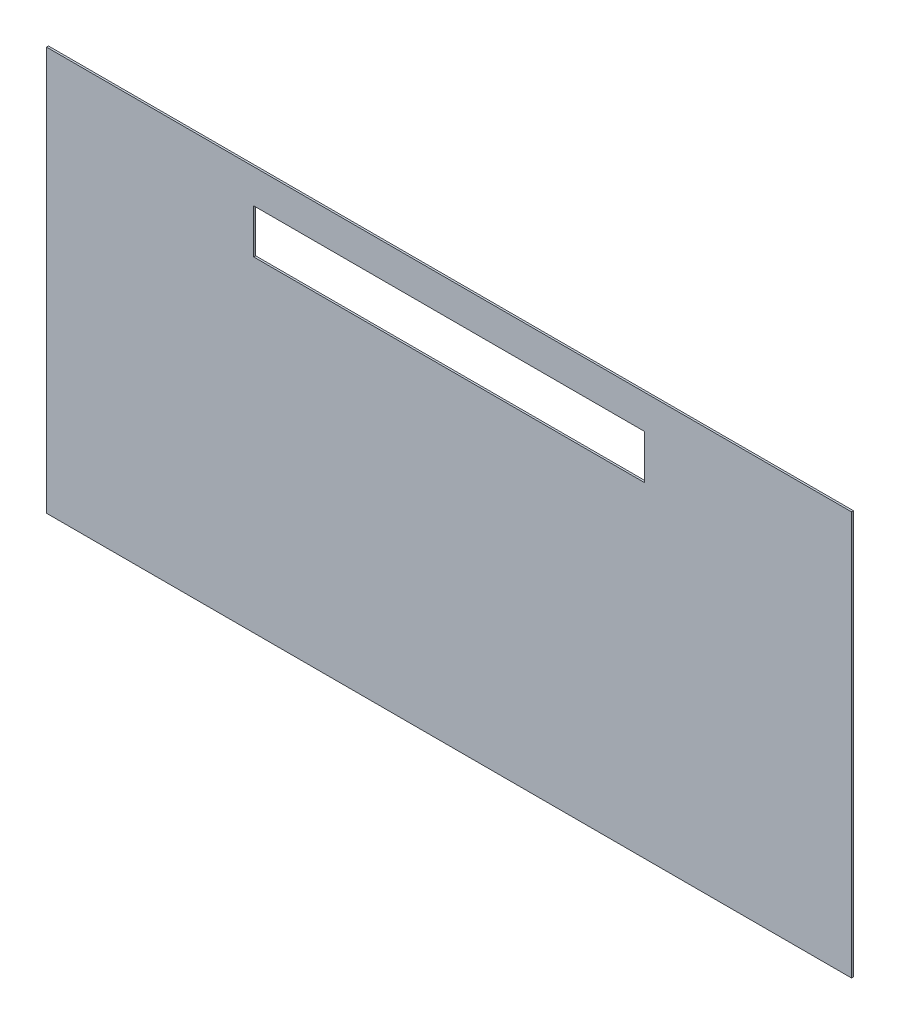
SolidWorks part; units mm, degrees
ref_plane "Front Plane" through (0, 0, 0) normal (0, 0, 1) x (1, 0, 0)
ref_plane "Top Plane" through (0, 0, 0) normal (0, 1, 0) x (1, 0, 0)
ref_plane "Right Plane" through (0, 0, 0) normal (1, 0, 0) x (0, 0, -1)
other "Configuration Table"
sketch "Sketch1" plane through (0, 0, 0) normal (0, 0, 1) x (1, 0, 0)
  line L1 (0, 0) -> (618, 0)
  line L2 (0, 0) -> (0, 310)
  line L3 (0, 310) -> (618, 310)
  line L4 (618, 0) -> (618, 310)
extrude "CEK_1L_on_dis_sac_1.5_1" add sketch "Sketch1" along normal blind 1.5 from offset 38.5 separate body
sketch "Sketch2" plane through (0, 0, 0) normal (0, 0, 1) x (1, 0, 0)
  line L1 (159, 250) -> (459, 250)
  line L2 (159, 250) -> (159, 284)
  line L3 (159, 284) -> (459, 284)
  line L4 (459, 250) -> (459, 284)
extrude "CEK_1L_on_dis_sac_1.5_2" cut sketch "Sketch2" along normal blind 14 from offset 27
